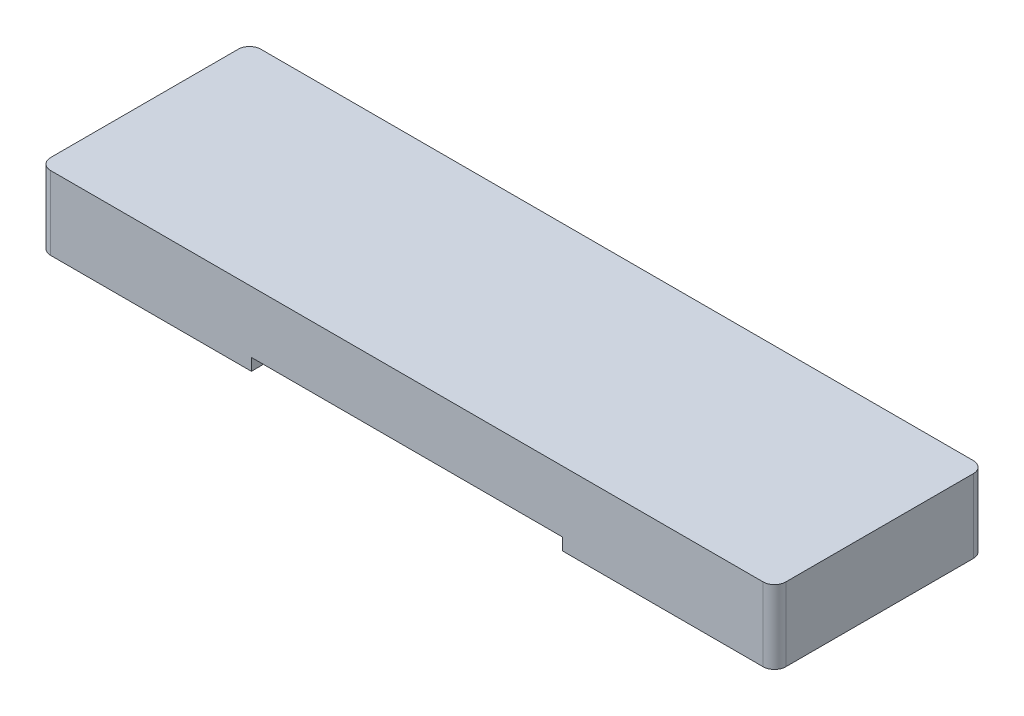
SolidWorks part; units mm, degrees
ref_plane "Front Plane" through (0, 0, 0) normal (0, 0, 1) x (1, 0, 0)
ref_plane "Top Plane" through (0, 0, 0) normal (0, 1, 0) x (1, 0, 0)
ref_plane "Right Plane" through (0, 0, 0) normal (1, 0, 0) x (0, 0, -1)
sketch "Sketch1" plane through (0, 0, 0) normal (0, 0, 1) x (1, 0, 0)
  line L0 (0, 0) -> (130, 0)
  line L1 (0, 0) -> (0, 13)
  line L2 (0, 13) -> (130, 13)
  line L3 (130, 13) -> (130, 0)
  dimension "D1" = 130
  dimension "D2" = 13
extrude "Boss-Extrude1" add sketch "Sketch1" against normal blind 37.17
shell "Shell1" thickness 2
sketch "Sketch2" plane through (0, 0, 0) normal (0, 0, 1) x (1, 0, 0)
  line L0 (0, 0) -> (130, 0) construction
  line L1 (37.5, 0) -> (92.5, 0)
  line L2 (37.5, 0) -> (37.5, 2.1338)
  line L3 (37.5, 2.1338) -> (92.5, 2.1338)
  line L4 (92.5, 0) -> (92.5, 2.1338)
  line L5 (37.5, -0.1548) -> (37.5, -15.1548) construction
  line L7 (92.5, -15.1548) -> (92.5, -0.1548) construction
  dimension "D1" = 2.1338
extrude "Cut-Extrude1" cut sketch "Sketch2" against normal blind 5
fillet "Fillet1" radius 2 4 edges at (0, 6.5, -37.17) (0, 6.5, 0) (130, 6.5, -37.17) (130, 6.5, 0)
